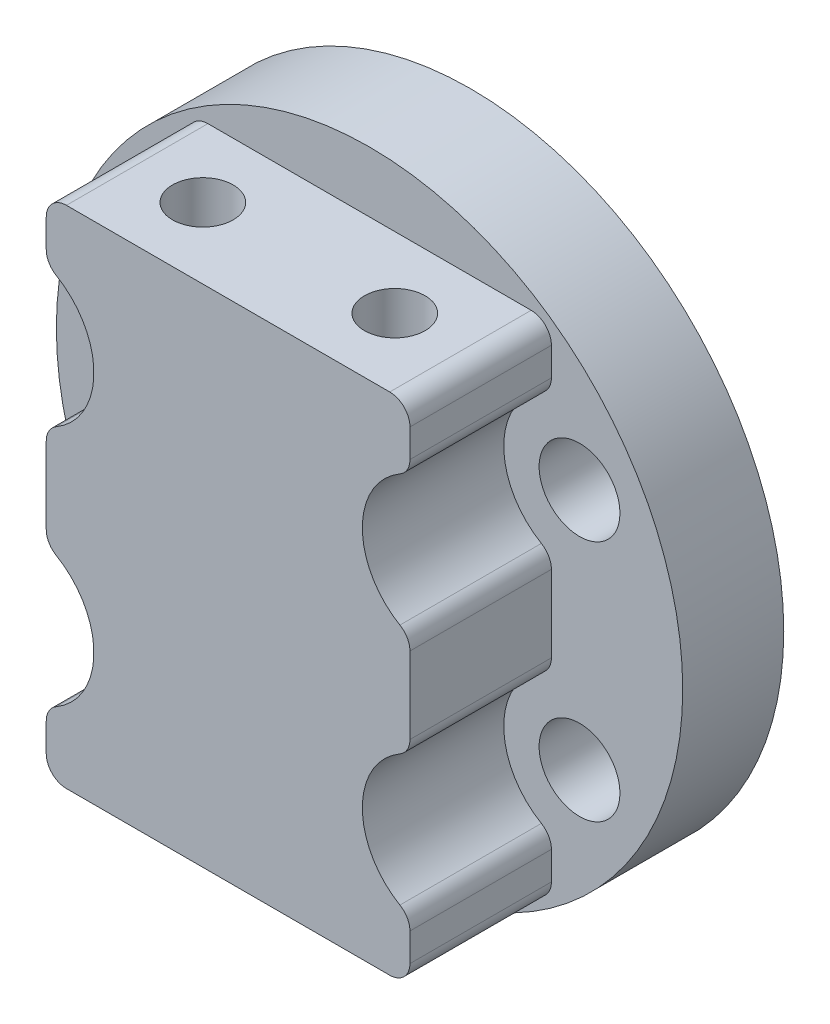
SolidWorks part; units mm, degrees
ref_plane "前视基准面" through (0, 0, 0) normal (0, 0, 1) x (1, 0, 0)
ref_plane "上视基准面" through (0, 0, 0) normal (0, 1, 0) x (1, 0, 0)
ref_plane "右视基准面" through (0, 0, 0) normal (1, 0, 0) x (0, 0, -1)
other "Configuration Table"
sketch "草图1" plane through (0, 0, 0) normal (0, 0, 1) x (1, 0, 0)
  line L0 (0, 12) -> (0, 0) construction
  line L1 (0, 0) -> (4.75, 8.2272) construction
  circle A0 centre (0, 12) radius 2 construction
  circle A1 centre (10.3923, 6) radius 2
  circle A2 centre (10.3923, -6) radius 2
  circle A3 centre (0, -12) radius 2 construction
  circle A4 centre (-10.3923, -6) radius 2
  circle A5 centre (-10.3923, 6) radius 2
  circle A6 centre (4.75, 8.2272) radius 2.15
  circle A7 centre (4.75, -8.2272) radius 2.15
  circle A8 centre (-9.5, 0) radius 2.15
  circle A9 centre (0, 0) radius 15.5
  circle A10 centre (0, 0) radius 8.5
  point P15 (0, 0)
  point P23 (0, 0)
  dimension "D1" = 4
  dimension "D4" = 4.3
  dimension "D8" = 31
  dimension "D9" = 17
  dimension "D2" = 12
  dimension "D5" = 30
  dimension "D6" = 9.5
  dimension "D3" = 6
  dimension "D7" = 3
extrude "凸台-拉伸1" add sketch "草图1" along normal blind 3 contours A9 A10 A6 A7 A8 A0 A1 A2 A3 A4 A5
fillet "圆角1" radius 3 6 edges at (-8.3093, 1.7902, 1.5) (-8.3093, -1.7902, 1.5) (2.6043, -8.0912, 1.5) (5.705, -6.301, 1.5) (5.705, 6.301, 1.5) (2.6043, 8.0912, 1.5)
sketch "草图5" plane through (0, 0, 3) normal (0, 0, 1) x (1, 0, 0)
  circle A0 centre (-10.3923, -6) radius 2 construction
  circle A1 centre (0, 0) radius 15.5
  circle A2 centre (0, 0) radius 15.5
  circle A4 centre (10.3923, -6) radius 2 construction
  circle A8 centre (-10.3923, -6) radius 2
  circle A10 centre (10.3923, -6) radius 2
  circle A14 centre (10.3923, 6) radius 2 construction
  circle A15 centre (-10.3923, 6) radius 2 construction
  circle A16 centre (10.3923, 6) radius 2
  circle A17 centre (-10.3923, 6) radius 2
  dimension "D1" = 0
extrude "凸台-拉伸3" add sketch "草图5" along normal blind 2
sketch "草图7" plane through (0, 0, 5) normal (0, 0, 1) x (1, 0, 0)
  line L1 (-9, 12.5) -> (9, 12.5)
  line L2 (-9, 12.5) -> (-9, -12.5)
  line L3 (-9, -12.5) -> (9, -12.5)
  line L4 (9, 12.5) -> (9, -12.5)
  line L5 (-9, 12.5) -> (9, -12.5) construction
  line L6 (-9, -12.5) -> (9, 12.5) construction
  circle A0 centre (-10.3923, 6) radius 3.75
  circle A1 centre (10.3923, 6) radius 2
  circle A2 centre (10.3923, 6) radius 2
  circle A3 centre (-10.3923, 6) radius 2
  circle A4 centre (-10.3923, 6) radius 2
  circle A5 centre (-10.3923, -6) radius 2
  circle A6 centre (-10.3923, -6) radius 2
  circle A7 centre (10.3923, -6) radius 2
  circle A8 centre (10.3923, -6) radius 2
  circle A9 centre (-10.3923, -6) radius 3.75
  circle A10 centre (10.3923, 6) radius 3.75
  circle A11 centre (10.3923, -6) radius 3.75
  circle A13 centre (0, 0) radius 15.5
  circle A14 centre (0, 0) radius 15.5
  point P20 (0, 0)
  dimension "D7" = 18
  dimension "D8" = 25
  dimension "D1" = 0
  dimension "D2" = 0
  dimension "D3" = 0
  dimension "D4" = 0
  dimension "D5" = 1.75
  dimension "D6" = 1.75
  dimension "D9" = 0
extrude "凸台-拉伸5" add sketch "草图7" along normal blind 7 contours A11 L4 A10 L1 L2 A0 A9 L3
fillet "圆角4" radius 1 12 edges at (9, -2.518, 8.5) (9, -9.482, 8.5) (9, 9.482, 8.5) (9, 2.518, 8.5) (9, 12.5, 8.5) (-9, 2.518, 8.5) (-9, 9.482, 8.5) (-9, -9.482, 8.5) (-9, -2.518, 8.5) (-9, -12.5, 8.5) (9, -12.5, 8.5) (-9, 12.5, 8.5)
sketch "草图8" plane through (0, 12.5, 0) normal (0, 1, 0) x (1, 0, 0)
  line L0 (-8, -8.5) -> (8, -8.5) construction
  line L1 (-8, -5) -> (-8, -12) construction
  line L2 (8, -12) -> (8, -5) construction
  line L3 (0, -12) -> (0, 0) construction
  line L4 (-8, -12) -> (8, -12) construction
  circle A0 centre (-4.75, -8.5) radius 1.5
  circle A1 centre (4.75, -8.5) radius 1.5
  point P13 (0, 0)
  dimension "D1" = 3
  dimension "D2" = 9.5
extrude "切除-拉伸3" cut sketch "草图8" against normal through all
